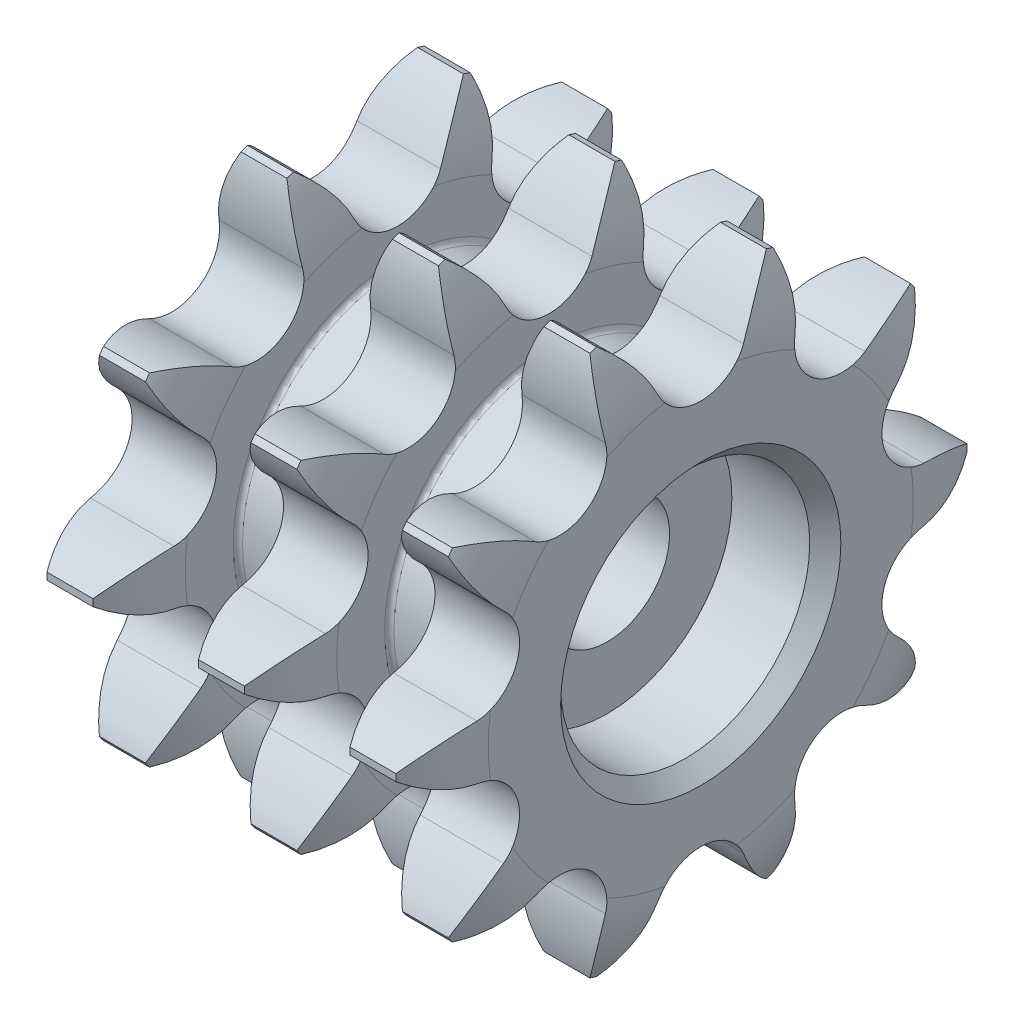
SolidWorks part; units mm, degrees
material "1.0503 (C45)"
ref_plane "Plane1" through (0, 0, 0) normal (0, 0, 1) x (1, 0, 0)
ref_plane "Plane2" through (0, 0, 0) normal (0, 1, 0) x (1, 0, 0)
ref_plane "Plane3" through (0, 0, 0) normal (1, 0, 0) x (0, 0, -1)
sketch "Clipboard" plane through (0, 0, 0) normal (0, 1, 0) x (1, 0, 0)
  line L0 (0, 0) -> (18.7606, -3.308)
  line L1 (-15, 0) -> (100, 0) construction
  line L2 (0, 0) -> (-1.641, 1.8547)
  line L3 (0, 0) -> (-17.7946, 6.8012)
  line L4 (0, 0) -> (3.0529, 0.5383)
  line L5 (0, 0) -> (-46.8476, -17.4728)
  line L6 (0, 0) -> (-41.2678, -27.8435)
  line L7 (-1.641, 1.8547) -> (49.0096, 13.5484)
  line L8 (-76.2, 38.1) -> (-75.5, 38.1)
  line L9 (-73.7108, 43.4516) -> (-73.1215, 43.5647)
  line L10 (-74.2736, 17.9847) -> (-54.8136, 17.9847)
  circle A0 centre (0, 0) radius 6.035
  circle A1 centre (0, 0) radius 20.4667
  circle A2 centre (0, 0) radius 37.5
  dimension "Dr" = 12.07
  dimension "MHD" = 40.9334
  dimension "Hub_dia" = 75
  dimension "Num_teeth" = 10
  dimension "Pitch" = 19.05
  dimension "Width" = 3.1
  dimension "Side_relief" = 2.4765
  dimension "Side_radius" = 19.05
  dimension "Overall_len" = 50
  dimension "Show_teeth" = 10
  dimension "Thickness" = 49.7824
  dimension "OAL" = 51.9829
  dimension "T_dim" = 0.7
  dimension "Fillet_rad" = 0.6
  dimension "Face_width" = 10.862
  dimension "Num_strands" = 3
  dimension "Transv_pitch" = 19.46
  dimension "Plate_wid" = 16.13
sketch "BasProSke" plane through (0, 0, 0) normal (0, 1, 0) x (1, 0, 0)
  line L0 (-10, 0) -> (60, 0) construction
  line L1 (0, 0) -> (0, 27.3022)
  line L2 (0, 0) -> (49.7824, 0)
  line L3 (49.7824, 0) -> (49.7824, 27.3022)
  line L4 (47.3059, 36.6948) -> (2.4765, 36.6948)
  arc A0 (0, 27.3022) -> (2.4765, 36.6948) centre (19.05, 27.3022) cw
  arc A1 (49.7824, 27.3022) -> (47.3059, 36.6948) centre (30.7324, 27.3022) ccw
  dimension "Thickness" = 49.7824
  dimension "D1" = 19.05
  dimension "G1" = 2.4765
  dimension "G2" = 2.4765
  dimension "Diameter" = 73.3896
revolve "Base-Revolve" add sketch "BasProSke" angle 360 about L0
sketch "GrvSke" plane through (0, 0, 0) normal (0, 1, 0) x (1, 0, 0)
  line L0 (10.8624, 27.3022) -> (10.8624, 21.1473)
  line L1 (11.4624, 20.5473) -> (18.86, 20.5473)
  line L2 (19.46, 21.1473) -> (19.46, 27.3022)
  line L3 (8.3859, 36.6948) -> (21.9365, 36.6948)
  line L4 (15.1612, 0) -> (15.1612, 52.07) construction
  line L5 (-10, 0) -> (60, 0) construction
  line L6 (0, 0) -> (35.56, 0) construction
  arc A0 (19.46, 27.3022) -> (21.9365, 36.6948) centre (38.51, 27.3022) cw
  arc A1 (10.8624, 27.3022) -> (8.3859, 36.6948) centre (-8.1876, 27.3022) ccw
  arc A2 (10.8624, 21.1473) -> (11.4624, 20.5473) centre (11.4624, 21.1473) ccw
  arc A3 (18.86, 20.5473) -> (19.46, 21.1473) centre (18.86, 21.1473) ccw
  dimension "Fillet_rad" = 0.6
  dimension "D1" = 19.05
  dimension "G1" = 2.4765
  dimension "Diameter" = 73.3896
  dimension "Grv_diam" = 41.0947
  dimension "Offset" = 15.1612
  dimension "Grv_width" = 8.5976
revolve "Groove" cut sketch "GrvSke" angle 360 about L6
pattern_linear "Grooves" count 2 spacing 19.46 along (1, 0, 0) of "Groove"
sketch "TooCutSke" plane through (0, 0, 0) normal (1, 0, 0) x (0, 0, -1)
  line L0 (0, 30.8839) -> (5.5465, 28.3562) construction
  line L1 (0, 0) -> (0, 107) construction
  line L2 (0, 30.8839) -> (-10, 30.8839) construction
  line L3 (0, 30.8839) -> (-5.5465, 28.3562) construction
  arc A0 (5.5465, 28.3562) -> (11.4136, 35.4003) centre (21.3624, 21.1485) cw
  arc A1 (5.5465, 28.3562) -> (-5.5465, 28.3562) centre (0, 30.8839) cw
  arc A2 (-5.5465, 28.3562) -> (-11.4136, 35.4003) centre (-21.3624, 21.1485) ccw
  arc A3 (11.4136, 35.4003) -> (-11.4136, 35.4003) centre (0, 0) ccw
  dimension "R1" = 6.0953
  dimension "R2" = 17.3808
  dimension "Overcut" = 37.1948
  dimension "Seat_radius" = 30.8839
  dimension "X" = 131
extrude "ToothCut" cut sketch "TooCutSke" along normal through all
pattern_circular "TeethCuts" count 10 every 36 about axis through (-10, 0, 0) along (1, 0, 0) of "ToothCut"
sketch "HubNeaOneSke" plane through (0, 0, 0) normal (-1, 0, 0) x (0, 0, 1)
  circle A0 centre (0, 0) radius 20.4667
  dimension "Diameter" = 40.9334
extrude "HubNearOne" [suppressed] add sketch "HubNeaOneSke" along normal blind 2.2005
fillet "HubNearOneFillet" [suppressed] radius 0.6
sketch "HubNeaBotSke" plane through (0, 0, 0) normal (-1, 0, 0) x (0, 0, 1)
  circle A0 centre (0, 0) radius 20.4667
  dimension "Diameter" = 40.9334
extrude "HubNearBoth" [suppressed] add sketch "HubNeaBotSke" along normal blind 1.1003
fillet "HubNearBothFillet" [suppressed] radius 0.6
ref_plane "FarPln" through (49.7824, 0, 0) normal (1, 0, 0) x (0, 0, -1)
sketch "HubFarSke" plane through (49.7824, 0, 0) normal (1, 0, 0) x (0, 0, -1)
  circle A0 centre (0, 0) radius 20.4667
  dimension "Diameter" = 40.9334
extrude "HubFar" [suppressed] add sketch "HubFarSke" along normal blind 1.1003
fillet "HubFarFillet" [suppressed] radius 0.6
sketch "BorSke" plane through (0, 0, 0) normal (1, 0, 0) x (0, 0, -1)
  circle A0 centre (0, 0) radius 2
  dimension "Diameter" = 4
extrude "Bore" cut sketch "BorSke" along normal mid plane 103.9658
sketch "KeySke" plane through (0, 0, 0) normal (1, 0, 0) x (0, 0, -1)
  line L0 (-0.8, 0) -> (-0.8, 2.7)
  line L1 (-0.8, 2.7) -> (0.8, 2.7)
  line L2 (0.8, 2.7) -> (0.8, 0)
  line L3 (0, 0) -> (0, 34) construction
  line L4 (-0.8, 0) -> (0.8, 0)
  dimension "Offset" = 2.7
  dimension "Width" = 1.6
extrude "Keyway" [suppressed] cut sketch "KeySke" along normal mid plane 103.9658
pattern_circular "Keyway2" [suppressed] count 2 every 90 about axis through (-10, 0, 0) along (1, 0, 0)
sketch "Sketch1" plane through (49.7824, 0, 0) normal (1, 0, 0) x (0, 0, -1)
  circle A0 centre (0, 0) radius 8
  dimension "D1" = 16
extrude "Cut-Extrude1" cut sketch "Sketch1" against normal through all
sketch "Sketch2" plane through (0, 0, 0) normal (-1, 0, 0) x (0, 0, 1)
  line L0 (-9.5, 12.5) -> (9.5, 12.5)
  line L1 (-12.5, 9.5) -> (-12.5, -9.5)
  line L2 (12.5, 9.5) -> (12.5, -9.5)
  line L3 (-9.5, -12.5) -> (9.5, -12.5)
  line L4 (-12.5, 12.5) -> (12.5, -12.5) construction
  line L5 (12.5, 12.5) -> (-12.5, -12.5) construction
  arc A0 (9.5, 12.5) -> (12.5, 9.5) centre (9.5, 9.5) cw
  arc A1 (12.5, -9.5) -> (9.5, -12.5) centre (9.5, -9.5) cw
  arc A2 (-12.5, -9.5) -> (-9.5, -12.5) centre (-9.5, -9.5) ccw
  arc A3 (-12.5, 9.5) -> (-9.5, 12.5) centre (-9.5, 9.5) cw
  point P1 (0, 0)
  dimension "D2" = 3
  dimension "D1" = 25
extrude "Cut-Extrude2" cut sketch "Sketch2" against normal blind 25
sketch "Sketch3" plane through (49.7824, 0, 0) normal (1, 0, 0) x (0, 0, -1)
  circle A0 centre (0, 0) radius 16
  dimension "D1" = 32
extrude "Cut-Extrude3" cut sketch "Sketch3" against normal blind 12
chamfer "Chamfer1" distance 2 angle 45 1 edges at (49.7824, 0, -16)
chamfer "Chamfer2" distance 3 angle 45 1 edges at (25, 0, -8)
equation "' \"Pitch@Clipboard\" = 12.7"
equation "' \"Num_strands@Clipboard\" = 3"
equation "' \"Num_teeth@Clipboard\" = 9"
equation "' \"Hub_dia@Clipboard\" = 50"
equation "' \"Overall_len@Clipboard\" = 3"
equation "' \"Diameter@BorSke\" = 12"
equation "' \"T_dim@Clipboard\" = 1"
equation "' \"Width@KeySke\" = 2"
equation "' \"Dr@Clipboard\" = 8.51"
equation "' \"Face_width@Clipboard\" = 7.2"
equation "' \"Side_radius@Clipboard\" = 12.7"
equation "' \"Side_relief@Clipboard\" = 1.27"
equation "' \"Transv_pitch@Clipboard\" = 13.92"
equation "' \"Show_teeth@Clipboard\" = 9"
equation "' \"Fillet_rad@Clipboard\" = 0.6"
equation "' \"Plate_wid@Clipboard\" = 11.8"
equation "\"Num_teeth@Clipboard\" = int( \"Num_teeth@Clipboard\" )"
equation "\"Num_teeth@Clipboard\" = ((sgn( \"Num_teeth@Clipboard\" - 5.0)+1)*( \"Num_teeth@Clipboard\" - 5.0))/2 +5.0"
equation "\"Num_teeth@Clipboard\" = ((sgn( \"Num_teeth@Clipboard\" - 200.0)-1)*( \"Num_teeth@Clipboard\" - 200.0))/-2 +200.0"
equation "\"MHD@Clipboard\" = \"Pitch@Clipboard\" * (1.0 / tan(3.14159265 / \"Num_teeth@Clipboard\" )) - 1.05 * \"Plate_wid@Clipboard\" - 0.76"
equation "\"Thickness@Clipboard\"  = \"Face_width@Clipboard\" + (\"Num_strands@Clipboard\" - 1) * \"Transv_pitch@Clipboard\""
equation "\"OAL@Clipboard\" = \"Thickness@Clipboard\" + 2 * \"Fillet_rad@Clipboard\" + 1"
equation "\"MHD@Clipboard\" = ((sgn( \"MHD@Clipboard\" - \"Hub_dia@Clipboard\" )-1)*( \"MHD@Clipboard\" - \"Hub_dia@Clipboard\" ))/-2+ \"Hub_dia@Clipboard\""
equation "\"OAL@Clipboard\" = ((sgn( \"OAL@Clipboard\" - \"Overall_len@Clipboard\" )+1)*( \"OAL@Clipboard\" - \"Overall_len@Clipboard\" ))/2 + \"Overall_len@Clipboard\" + 0.0005"
equation "\"Num_teeth@TeethCuts\" = int( \"Show_teeth@Clipboard\" ) + 1"
equation "\"Num_teeth@TeethCuts\" = ((sgn( \"Num_teeth@TeethCuts\" - \"Num_teeth@Clipboard\" )-1)*( \"Num_teeth@TeethCuts\" - \"Num_teeth@Clipboard\" ))/-2+ \"Num_teeth@Clipboard\""
equation "\"Num_teeth@TeethCuts\" = ((sgn( \"Num_teeth@TeethCuts\" - 2.0)+1)*( \"Num_teeth@TeethCuts\" - 2.0))/2 +2.0"
equation "\"Angle@TeethCuts\" = 360.0 / \"Num_teeth@Clipboard\""
equation "\"Seat_radius@TooCutSke\" = ( \"Pitch@Clipboard\" / 2.0) / sin(3.14159265 / \"Num_teeth@Clipboard\" ) - \"Dr@Clipboard\" / 2.0 + \"Dr@Clipboard\" * 0.505"
equation "\"R1@TooCutSke\"  = \"Dr@Clipboard\" * 0.505"
equation "\"X@TooCutSke\" = 140.0 - (90.0 / \"Num_teeth@Clipboard\")"
equation "\"R2@TooCutSke\" = 0.12 * \"Dr@Clipboard\" * ( \"Num_teeth@Clipboard\" + 2.0)"
equation "\"Overcut@TooCutSke\" = 0.5 + 0.625 * \"Pitch@Clipboard\" - 0.5 * \"Dr@Clipboard\"  +  \"Pitch@Clipboard\" / 2.0 / sin(3.14159265 / \"Num_teeth@Clipboard\" )"
equation "\"Diameter@BasProSke\" = 2.0 * ( 0.625 * \"Pitch@Clipboard\" - 0.5 * \"Dr@Clipboard\"  +  \"Pitch@Clipboard\" / 2.0 / sin(3.14159265 / \"Num_teeth@Clipboard\" ))"
equation "\"Thickness@BasProSke\"  = \"Thickness@Clipboard\""
equation "\"G1@BasProSke\" =  \"Side_relief@Clipboard\""
equation "\"G2@BasProSke\" =  \"Side_relief@Clipboard\""
equation "\"D1@BasProSke\" =  \"Side_radius@Clipboard\""
equation "\"Diameter@GrvSke\" = \"Diameter@BasProSke\""
equation "\"G1@GrvSke\" = \"Side_relief@Clipboard\""
equation "\"D1@GrvSke\" = \"Side_radius@Clipboard\""
equation "\"Grv_diam@GrvSke\" =  \"Pitch@Clipboard\" * (1.0 / tan(3.14159265 / \"Num_teeth@Clipboard\" ))- 1.04 * \"Plate_wid@Clipboard\" - 0.76"
equation "\"Grv_width@GrvSke\" =  \"Transv_pitch@Clipboard\" - \"Face_width@Clipboard\""
equation "\"Offset@GrvSke\" = \"Grv_width@GrvSke\" / 2.0 + \"Face_width@Clipboard\""
equation "\"Fillet_rad@GrvSke\" = \"Fillet_rad@Clipboard\""
equation "\"Offset@Grooves\" = \"Transv_pitch@Clipboard\""
equation "\"Num_grvs@Grooves\" = \"Num_strands@Clipboard\""
equation "\"Num_grvs@Grooves\" = \"Num_grvs@Grooves\" - 1 * sgn( \"Num_grvs@Grooves\" -1)"
equation "\"Diameter@HubNeaOneSke\" = \"MHD@Clipboard\""
equation "\"Length@HubNearOne\" = \"OAL@Clipboard\" - \"Thickness@BasProSke\""
equation "\"Diameter@HubNeaBotSke\" = \"MHD@Clipboard\""
equation "\"Length@HubNearBoth\" = ( \"OAL@Clipboard\" - \"Thickness@BasProSke\" ) / 2.0"
equation "\"D1@HubNearOneFillet\" = \"Fillet_rad@Clipboard\""
equation "\"D1@HubNearBothFillet\" = \"Fillet_rad@Clipboard\""
equation "\"Thickness@FarPln\" = \"Thickness@BasProSke\""
equation "\"Diameter@HubFarSke\" = \"MHD@Clipboard\""
equation "\"Length@HubFar\" = ( \"OAL@Clipboard\" - \"Thickness@BasProSke\" ) / 2.0"
equation "\"D1@HubFarFillet\" = \"Fillet_rad@Clipboard\""
equation "\"D1@Bore\" = \"OAL@Clipboard\" * 2.0"
equation "\"D1@Keyway\" = \"OAL@Clipboard\" * 2.0"
equation "\"Offset@KeySke\" = \"T_dim@Clipboard\" + \"Diameter@BorSke\" / 2.0"
